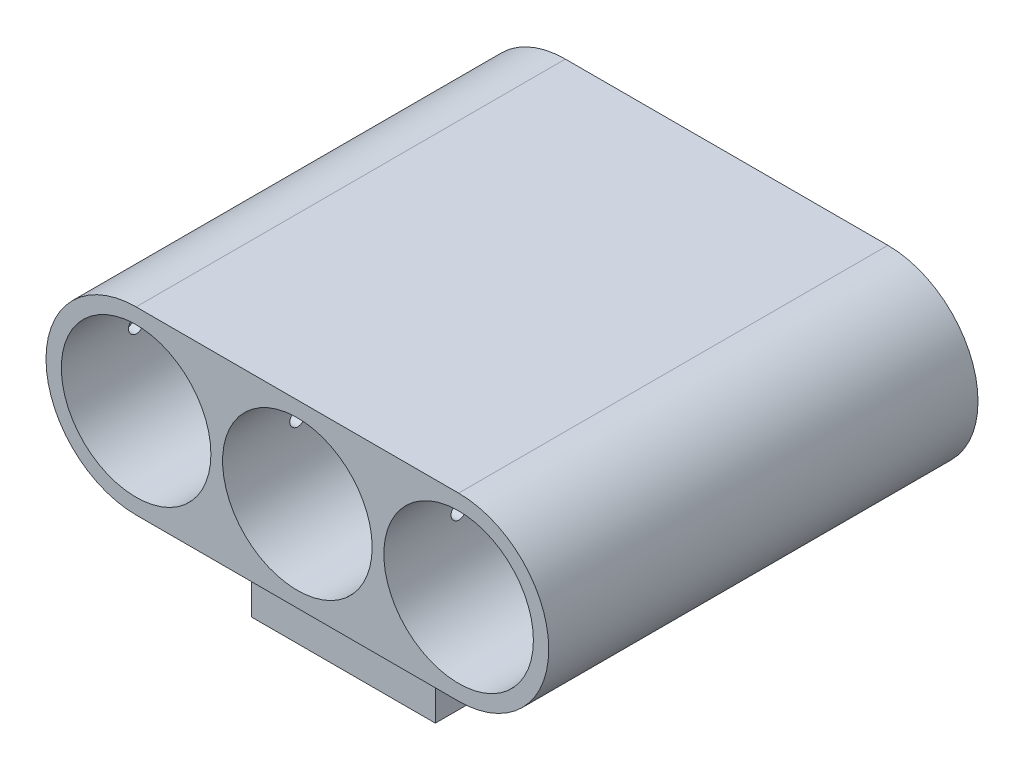
SolidWorks part; units mm, degrees
ref_plane "Front Plane" through (0, 0, 0) normal (0, 0, 1) x (1, 0, 0)
ref_plane "Top Plane" through (0, 0, 0) normal (0, 1, 0) x (1, 0, 0)
ref_plane "Right Plane" through (0, 0, 0) normal (1, 0, 0) x (0, 0, -1)
sketch "Sketch1" plane through (0, 0, 0) normal (0, 1, 0) x (1, 0, 0)
  line L1 (0.7303, 11) -> (12.7303, 11)
  line L2 (0.7303, 11) -> (0.7303, -11)
  line L3 (0.7303, -11) -> (12.7303, -11)
  line L4 (12.7303, 11) -> (12.7303, -11)
  dimension "D1" = 22
  dimension "D2" = 12
extrude "Boss-Extrude1" add sketch "Sketch1" along normal blind 5
sketch "Sketch2" plane through (0, 0, 11) normal (0, 0, 1) x (1, 0, 0)
  line L0 (-3.788, 10.8779) -> (17.2487, 10.8779) construction
  line L1 (-3.788, 16.7557) -> (17.2487, 16.7557)
  line L2 (-3.788, 5) -> (17.2487, 5)
  line L3 (0.7303, 5) -> (12.7303, 5) construction
  line L4 (6.7303, 0) -> (6.7303, 11.5962) construction
  line L5 (0.7303, 0) -> (12.7303, 0) construction
  arc A0 (-3.788, 16.7557) -> (-3.788, 5) centre (-3.788, 10.8779) ccw
  arc A1 (17.2487, 5) -> (17.2487, 16.7557) centre (17.2487, 10.8779) ccw
  circle A2 centre (17.2487, 10.8779) radius 4.8779
  circle A3 centre (6.7303, 10.8779) radius 4.8779
  circle A4 centre (-3.788, 10.8779) radius 4.8779
  point P2 (6.7303, 10.8779)
  point P19 (-3.788, 10.8779)
  dimension "D1" = 1
  dimension "D2" = 9.7557
extrude "Boss-Extrude2" add sketch "Sketch2" against normal blind 25 and the other way blind 3
ref_plane "Plane1" through (6.7303, 0, 0) normal (1, 0, 0) x (0, 0, -1)
sketch "Sketch4" plane through (6.7303, 0, 0) normal (1, 0, 0) x (0, 0, -1)
  line L0 (-14, 10.8779) -> (14, 10.8779) construction
  line L1 (-14, 15.7557) -> (-14, 6) construction
  line L2 (14, 6) -> (14, 15.7557) construction
  line L3 (-9.12, 15.7557) -> (-9.12, 6) construction
  line L4 (14, 15.7557) -> (-14, 15.7557) construction
  line L5 (-14, 6) -> (14, 6) construction
  circle A0 centre (-9.12, 10.8779) radius 0.5
  point P14 (0, 0)
  dimension "D2" = 1
  dimension "D1" = 4.88
extrude "Cut-Extrude1" cut sketch "Sketch4" along normal blind 16 and the other way blind 16
